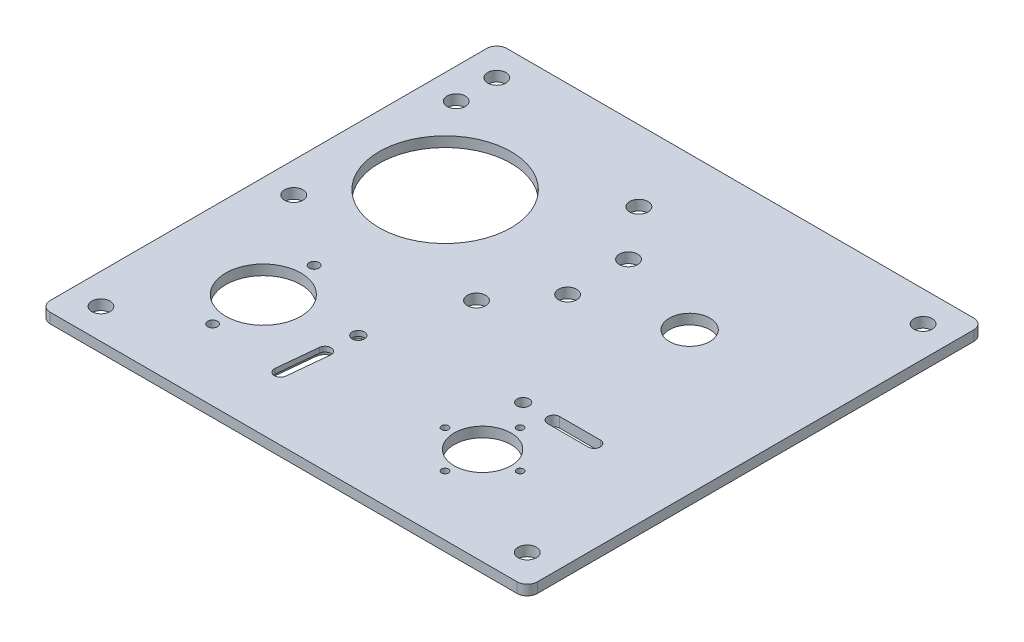
SolidWorks part; units mm, degrees
ref_plane "Front" through (0, 0, 0) normal (0, 0, 1) x (1, 0, 0)
ref_plane "Top" through (0, 0, 0) normal (0, 1, 0) x (1, 0, 0)
ref_plane "Right" through (0, 0, 0) normal (1, 0, 0) x (0, 0, -1)
sketch "Sketch1" plane through (0, 0, 0) normal (0, 1, 0) x (1, 0, 0)
  line L1 (0, 0) -> (230, 0)
  line L2 (0, 0) -> (0, 200)
  line L3 (0, 200) -> (230, 200)
  line L4 (230, 0) -> (230, 200)
  dimension "D1" = 200
  dimension "D2" = 230
extrude "Boss-Extrude1" add sketch "Sketch1" along normal blind 5
sketch "Sketch2" plane through (0, 5, 0) normal (0, 1, 0) x (1, 0, 0)
  line L0 (0, 102.5) -> (230, 102.5) construction
  line L1 (0, 200) -> (0, 0) construction
  line L2 (-19.6793, 100) -> (274.1504, 100) construction
  line L3 (50, 60) -> (169.9992, 48) construction
  line L4 (89.304, 51.0446) -> (87.3139, 31.1439) construction
  line L5 (92.2891, 50.7461) -> (90.299, 30.8454)
  line L6 (86.3189, 51.3432) -> (84.3288, 31.4424)
  line L7 (50, 149.55) -> (169.9992, 150) construction
  line L8 (169.9992, 150) -> (169.9992, 48) construction
  line L9 (0, 0) -> (230, 0) construction
  line L10 (0, 200) -> (0, 0) construction
  line L11 (230, 200) -> (0, 200) construction
  line L12 (88.3089, 41.0943) -> (93.2841, 90.8461) construction
  circle A0 centre (50, 60) radius 18.5
  arc A2 (92.2891, 50.7461) -> (86.3189, 51.3432) centre (89.304, 51.0446) ccw
  arc A3 (84.3288, 31.4424) -> (90.299, 30.8454) centre (87.3139, 31.1439) ccw
  circle A4 centre (169.9992, 48) radius 14
  circle A5 centre (169.9992, 150) radius 10
  circle A6 centre (50, 149.55) radius 15
  circle A7 centre (90.7965, 65.9702) radius 3
  point P13 (88.3089, 41.0943)
  dimension "D1" = 37
  dimension "D3" = 3
  dimension "D7" = 28
  dimension "D10" = 20
  dimension "D5" = 60
  dimension "D11" = 100
  dimension "D14" = 47.5
  dimension "D17" = 50.45
  dimension "D18" = 30
  dimension "D21" = 10
  dimension "D22" = 6
  dimension "D8" = 52
  dimension "D2" = 5
  dimension "D4" = 50
  dimension "D6" = 40
  dimension "D12" = 120
  dimension "D13" = 102.5
  dimension "D15" = 47.05
  dimension "D16" = 50
  dimension "D19" = 50
  dimension "D20" = 20
extrude "Cut-Extrude1" cut sketch "Sketch2" against normal through all
hole_wizard "M3 Clearance Hole1" positions "Sketch3" profile "Sketch4" hole size "M3" standard "ISO" end condition through all
sketch "Sketch3" plane through (0, 5, 0) normal (0, 1, 0) x (1, 0, 0)
  line L0 (0, 100) -> (162.5265, 100) construction
  line L1 (0, 200) -> (0, 0) construction
  circle A0 centre (50, 60) radius 25 construction
  circle A1 centre (169.9992, 48) radius 18.5 construction
  circle A2 centre (169.9992, 150) radius 29 construction
  point P9 (50, 35)
  point P16 (50, 85)
  point P21 (169.9992, 66.5)
  point P23 (169.9992, 29.5)
  point P25 (188.4992, 48)
  point P27 (151.4992, 48)
  dimension "D1" = 50
  dimension "D2" = 37
  dimension "D3" = 58
sketch "Sketch4" plane through (151.4992, 5, -48) normal (1, 0, 0) x (0, 0, 1)
  line L0 (0, 0) -> (0, 5)
  line L1 (0, 5) -> (1.7, 5)
  line L2 (1.7, 5) -> (1.7, 0)
  line L5 (1.7, 0) -> (0, 0)
  line L11 (0, -6.35) -> (0, 107.95) construction
  dimension "Thru Hole Dia." = 3.4
  dimension "Thru Hole Depth" = 5
ref_plane "Plane1" through (0, 0, -100) normal (0, 0, 1) x (1, 0, 0)
sketch "Sketch5" plane through (0, 5, 0) normal (0, 1, 0) x (1, 0, 0)
  line L0 (-14.3101, 5) -> (264.9413, 5) construction
  line L1 (0, 0) -> (230, 0) construction
  line L2 (20, 5) -> (40, 5)
  line L3 (20, 5) -> (20, 10)
  line L4 (20, 10) -> (40, 10)
  line L5 (40, 5) -> (40, 10)
  line L6 (0, 200) -> (0, 0) construction
  line L7 (60, 5) -> (60, 10)
  line L8 (60, 5) -> (80, 5)
  line L9 (80, 5) -> (80, 10)
  line L10 (60, 10) -> (80, 10)
  line L11 (100, 5) -> (100, 10)
  line L12 (100, 5) -> (120, 5)
  line L13 (120, 5) -> (120, 10)
  line L14 (100, 10) -> (120, 10)
  line L15 (140, 5) -> (140, 10)
  line L16 (140, 5) -> (160, 5)
  line L17 (160, 5) -> (160, 10)
  line L18 (140, 10) -> (160, 10)
  line L19 (180, 5) -> (180, 10)
  line L20 (180, 5) -> (200, 5)
  line L21 (200, 5) -> (200, 10)
  line L22 (180, 10) -> (200, 10)
  dimension "D1" = 5
  dimension "D2" = 20
  dimension "D3" = 5
  dimension "D4" = 20
  dimension "D5" = 5
extrude "Slots" [suppressed] cut sketch "Sketch5" against normal through all
ref_plane "Plane3" through (0, 0, -56) normal (0, 0, 1) x (1, 0, 0)
mirror "Mirror2" [suppressed] about plane through (0, 0, -56) normal (0, 0, 1)
sketch "Sketch6" plane through (0, 5, 0) normal (0, 1, 0) x (1, 0, 0)
  line L0 (184.9992, 78) -> (149.3355, 78) construction
  line L2 (169.9992, 150) -> (169.9992, 48) construction
  line L3 (174.9992, 78) -> (194.9992, 78) construction
  line L4 (174.9992, 81) -> (194.9992, 81)
  line L5 (174.9992, 75) -> (194.9992, 75)
  arc A0 (174.9992, 81) -> (174.9992, 75) centre (174.9992, 78) ccw
  arc A1 (194.9992, 75) -> (194.9992, 81) centre (194.9992, 78) ccw
  circle A2 centre (159.9992, 78) radius 3
  point P8 (184.9992, 78)
  dimension "D2" = 3
  dimension "D5" = 6
  dimension "D6" = 10
  dimension "D1" = 20
  dimension "D3" = 30
  dimension "D4" = 5
extrude "Cut-Extrude3" cut sketch "Sketch6" against normal through all
sketch "Sketch7" plane through (0, 5, 0) normal (0, 1, 0) x (1, 0, 0)
  circle A0 centre (50, 149.55) radius 32.5
  dimension "D1" = 65
extrude "Cut-Extrude4" cut sketch "Sketch7" against normal through all
fillet "Fillet1" [suppressed] radius 5
sketch "Sketch8" plane through (0, 5, 0) normal (0, 1, 0) x (1, 0, 0)
  line L0 (0, 200) -> (0, 0) construction
  line L1 (230, 0) -> (240, 0)
  line L2 (230, 0) -> (230, 200)
  line L3 (230, 200) -> (240, 200)
  line L4 (240, 0) -> (240, 200)
  line L5 (230, 200) -> (0, 200) construction
  dimension "D1" = 240
extrude "Boss-Extrude2" add sketch "Sketch8" against normal up to surface (5 mm away) up to face at (50, 0, -117.05)
sketch "Sketch9" plane through (0, 5, 0) normal (0, 1, 0) x (1, 0, 0)
  line L1 (0, 200) -> (240, 200)
  line L2 (0, 200) -> (0, 225)
  line L3 (0, 225) -> (240, 225)
  line L4 (240, 200) -> (240, 225)
  dimension "D1" = 25
extrude "Boss-Extrude3" add sketch "Sketch9" against normal up to surface (5 mm away) up to face at (50, 0, -117.05)
ref_plane "Plane2" through (0, 0, -112.5) normal (0, 0, -1) x (-1, 0, 0)
mirror "Mirror3" [suppressed] about plane through (0, 0, -112.5) normal (0, 0, -1)
hole_wizard "M8 Clearance Hole1" positions "Sketch12" profile "Sketch11" hole size "M8" standard "ISO" end condition through all
sketch "Sketch12" plane through (0, 5, 0) normal (0, 1, 0) x (1, 0, 0)
  line L0 (120, 225) -> (120, 0) construction
  line L1 (240, 225) -> (0, 225) construction
  line L2 (0, 0) -> (240, 0) construction
  line L5 (0, 112.5) -> (240, 112.5) construction
  line L6 (0, 225) -> (0, 0) construction
  line L7 (240, 0) -> (240, 225) construction
  point P0 (15, 210)
  point P22 (225, 210)
  point P24 (225, 15)
  point P25 (15, 15)
  dimension "D1" = 15
  dimension "D2" = 15
sketch "Sketch11" plane through (15, 5, -210) normal (1, 0, 0) x (0, 0, 1)
  line L0 (0, 0) -> (0, 5)
  line L1 (0, 5) -> (4.5, 5)
  line L2 (4.5, 5) -> (4.5, 0)
  line L5 (4.5, 0) -> (0, 0)
  line L11 (0, -6.35) -> (0, 107.95) construction
  dimension "Thru Hole Dia." = 9
  dimension "Thru Hole Depth" = 5
hole_wizard "M5 Clearance Hole1" [suppressed] positions "Sketch13" profile "Sketch14" hole size "M5" standard "ISO"
sketch "Sketch13" plane through (0, 5, 0) normal (0, 1, 0) x (1, 0, 0)
  point P0 (169.904, 178.8)
  point P3 (140.904, 149.8)
  point P6 (198.904, 149.8)
  point P9 (169.904, 120.8)
sketch "Sketch14" plane through (169.904, 5, -178.8) normal (1, 0, 0) x (0, 0, 1)
  line L0 (0, 0) -> (0, 5)
  line L1 (0, 5) -> (2.75, 5)
  line L2 (2.75, 5) -> (2.75, 0)
  line L5 (2.75, 0) -> (0, 0)
  line L11 (0, -6.35) -> (0, 107.95) construction
  dimension "Thru Hole Dia." = 5.5
  dimension "Thru Hole Depth" = 5
fillet "Fillet2" radius 5 4 edges at (0, 2.5, -225) (240, 2.5, -225) (240, 2.5, 0) (0, 2.5, 0)
hole_wizard "M8 Clearance Hole2" positions "Sketch15" profile "Sketch16" hole size "M8" standard "ISO" end condition through all
sketch "Sketch15" plane through (0, 0, 0) normal (0, -1, 0) x (-1, 0, 0)
  line L0 (0, 220) -> (0, 5) construction
  line L1 (-235, 225) -> (-5, 225) construction
  line L2 (26.5892, 150) -> (-114.4256, 150) construction
  line L4 (-60, 254.5628) -> (-60, 120.4687) construction
  line L6 (0, 220) -> (0, 5) construction
  point P0 (-15, 190)
  point P16 (-105, 190)
  point P19 (-105, 110)
  point P20 (-15, 110)
  dimension "D1" = 15
  dimension "D2" = 35
  dimension "D3" = 60
  dimension "D4" = 40
sketch "Sketch16" plane through (15, 0, -190) normal (1, 0, 0) x (0, 0, -1)
  line L0 (0, 0) -> (0, 5)
  line L1 (0, 5) -> (4.5, 5)
  line L2 (4.5, 5) -> (4.5, 0)
  line L5 (4.5, 0) -> (0, 0)
  line L11 (0, -6.35) -> (0, 107.95) construction
  dimension "Thru Hole Dia." = 9
  dimension "Thru Hole Depth" = 5
hole_wizard "M4 Clearance Hole1" [suppressed] positions "Sketch17" profile "Sketch18" hole size "M4" standard "ISO"
sketch "Sketch17" [suppressed] plane through (0, 5, 0) normal (0, 1, 0) x (1, 0, 0)
  line L0 (169.904, 149.8) -> (133.1181, 113.0141) construction
  line L2 (140.904, 149.8) -> (169.904, 120.8) construction
  line L5 (131.3666, 121.8693) -> (141.9732, 111.2627) construction
  point P0 (131.3666, 121.8693)
  point P2 (141.9732, 111.2627)
  dimension "D1" = 15
  dimension "D2" = 7.5
  dimension "D3" = 47
sketch "Sketch18" plane through (131.3666, 5, -121.8693) normal (1, 0, 0) x (0, 0, 1)
  line L0 (0, 0) -> (0, 5)
  line L1 (0, 5) -> (2.25, 5)
  line L2 (2.25, 5) -> (2.25, 0)
  line L5 (2.25, 0) -> (0, 0)
  line L11 (0, -6.35) -> (0, 107.95) construction
  dimension "Thru Hole Dia." = 4.5
  dimension "Thru Hole Depth" = 5
hole_wizard "M8 Clearance Hole3" positions "Sketch19" profile "Sketch20" hole size "M8" standard "ISO" end condition through all
sketch "Sketch19" plane through (0, 5, 0) normal (0, 1, 0) x (1, 0, 0)
  line L0 (124.9, 165) -> (124.9, 135) construction
  line L2 (124.9, 150) -> (240, 150) construction
  line L3 (240, 5) -> (240, 220) construction
  circle A2 centre (169.9992, 150) radius 10 construction
  point P0 (124.9, 165)
  point P2 (124.9, 135)
  dimension "D2" = 0
  dimension "D1" = 115.1
  dimension "D3" = 30
sketch "Sketch20" plane through (124.9, 5, -165) normal (1, 0, 0) x (0, 0, 1)
  line L0 (0, 0) -> (0, 5)
  line L1 (0, 5) -> (4.5, 5)
  line L2 (4.5, 5) -> (4.5, 0)
  line L5 (4.5, 0) -> (0, 0)
  line L11 (0, -6.35) -> (0, 107.95) construction
  dimension "Thru Hole Dia." = 9
  dimension "Thru Hole Depth" = 5
sketch "Sketch21" plane through (0, 0, 0) normal (0, -1, 0) x (1, 0, 0)
  line L9 (82.3387, -31.6414) -> (84.3288, -51.5422)
  line L10 (94.2791, -50.5471) -> (92.2891, -30.6464)
  line L11 (82.3387, -31.6414) -> (84.3288, -51.5422)
  line L12 (94.2791, -50.5471) -> (92.2891, -30.6464)
  arc A5 (84.3288, -51.5422) -> (94.2791, -50.5471) centre (89.304, -51.0446) ccw
  arc A6 (92.2891, -30.6464) -> (82.3387, -31.6414) centre (87.3139, -31.1439) ccw
  arc A7 (84.3288, -51.5422) -> (94.2791, -50.5471) centre (89.304, -51.0446) ccw
  arc A8 (92.2891, -30.6464) -> (82.3387, -31.6414) centre (87.3139, -31.1439) ccw
  circle A9 centre (90.7965, -65.9702) radius 5
  circle A10 centre (90.7965, -65.9702) radius 5
  dimension "D1" = 2
  dimension "D2" = 2
extrude "Cut-Extrude5" cut sketch "Sketch21" against normal blind 2.5
sketch "Sketch22" plane through (0, 5, 0) normal (0, 1, 0) x (1, 0, 0)
  circle A0 centre (50, 85) radius 2.4
  circle A1 centre (50, 35) radius 2.4
  dimension "D1" = 4.8
  dimension "D2" = 4.8
extrude "Cut-Extrude6" cut sketch "Sketch22" against normal through all
